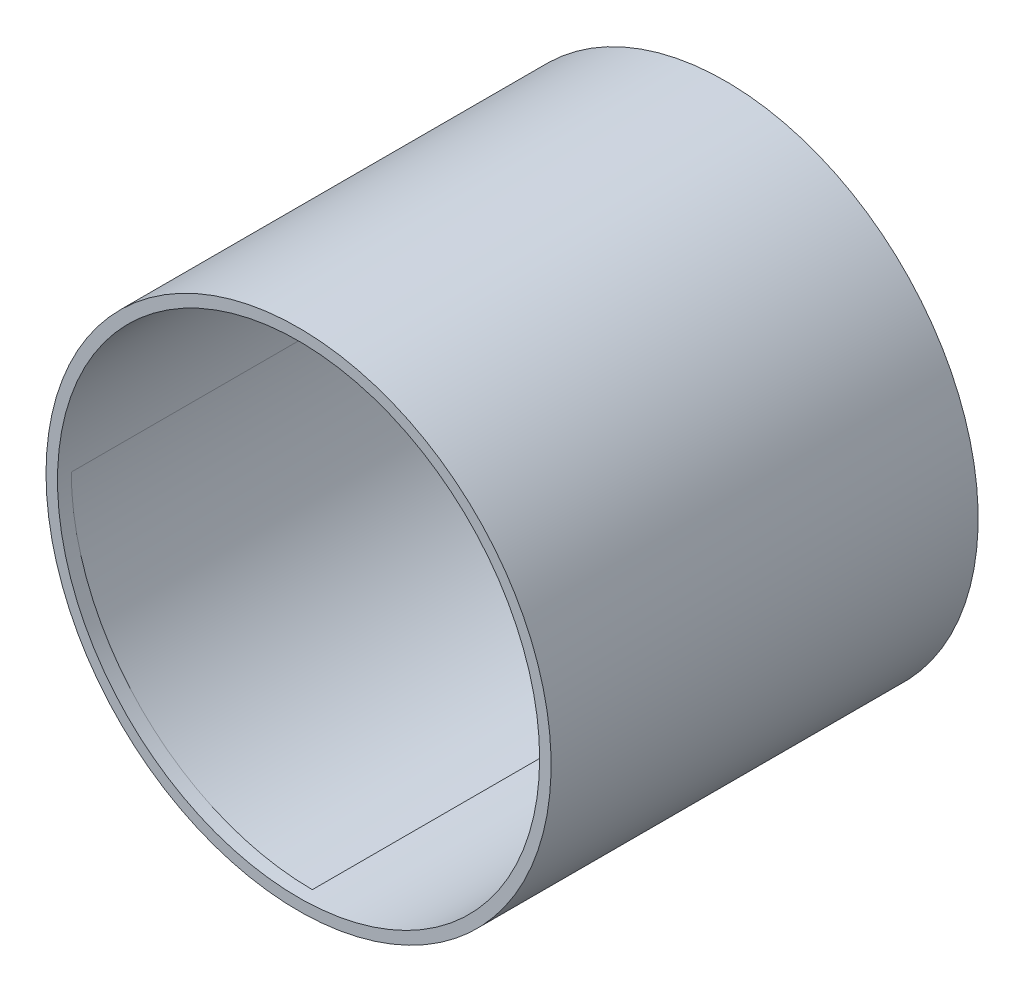
SolidWorks part; units mm, degrees
ref_plane "Přední rovina" through (0, 0, 0) normal (0, 0, 1) x (1, 0, 0)
ref_plane "Horní rovina" through (0, 0, 0) normal (0, 1, 0) x (1, 0, 0)
ref_plane "Pravá rovina" through (0, 0, 0) normal (1, 0, 0) x (0, 0, -1)
sketch "Skica1" plane through (0, 0, 0) normal (0, 0, 1) x (1, 0, 0)
  circle A0 centre (0, 0) radius 55
  dimension "D1" = 110
extrude "Přidat vysunutím1" add sketch "Skica1" along normal blind 93 contours A0
sketch "Skica3" plane through (0, 0, 93) normal (0, 0, 1) x (1, 0, 0)
  circle A0 centre (0, 0) radius 52.5
  dimension "D1" = 105
extrude "Odebrat vysunutím1" cut sketch "Skica3" against normal blind 90
sketch "Skica5" plane through (0, 0, 0) normal (0, 0, -1) x (-1, 0, 0)
  line L0 (0, -4.755) -> (0, -52.755)
  line L1 (4.7202, 0) -> (52.7202, 0)
  line L2 (4.7202, 0) -> (0, -4.755)
  circle A0 centre (0, 0) radius 2.5
  arc A1 (52.7202, 0) -> (0, -52.755) centre (-0.0348, 0) cw
  dimension "D1" = 5
  dimension "D5" = 52.755
  dimension "D2" = 48
  dimension "D3" = 48
  dimension "D4" = 6.7
extrude "Odebrat vysunutím5" cut sketch "Skica5" against normal blind 90
